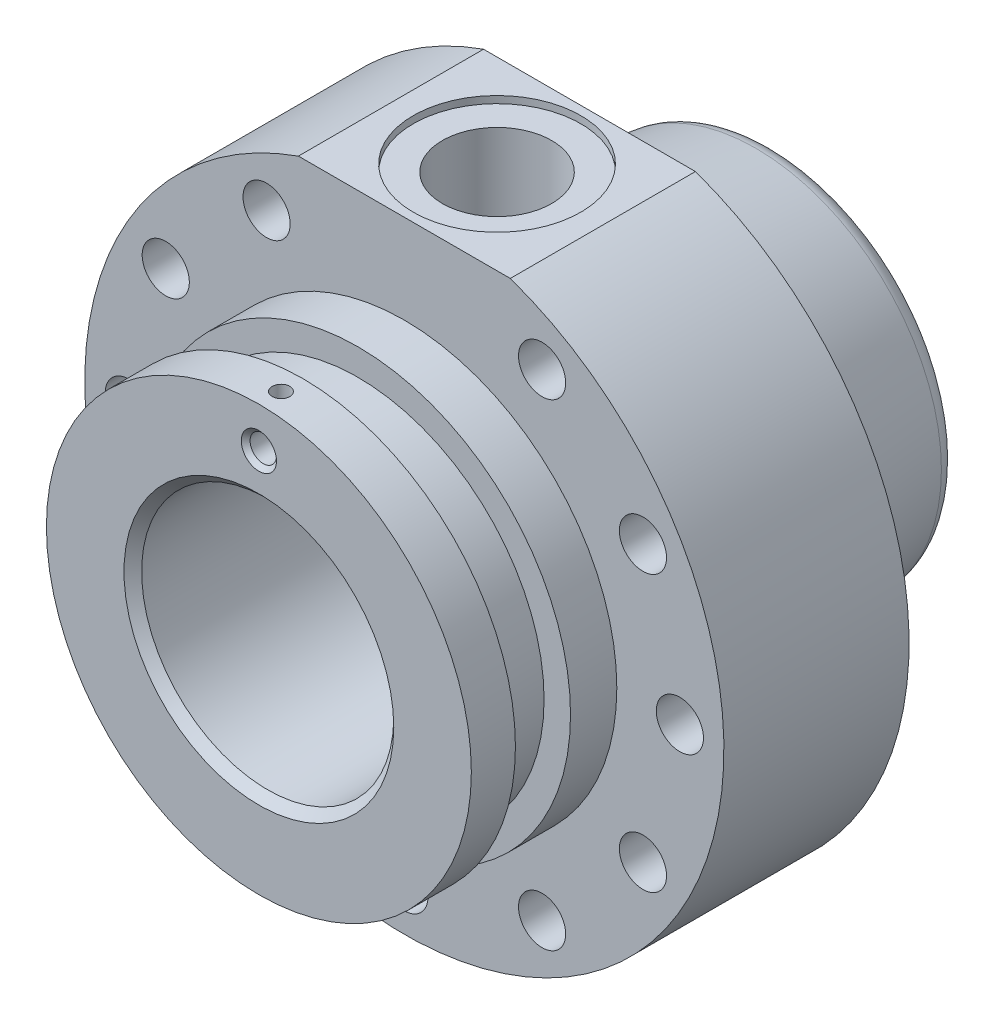
SolidWorks part; units mm, degrees
ref_plane "Płaszczyzna przednia" through (0, 0, 0) normal (0, 0, 1) x (1, 0, 0)
ref_plane "Płaszczyzna górna" through (0, 0, 0) normal (0, 1, 0) x (1, 0, 0)
ref_plane "Płaszczyzna prawa" through (0, 0, 0) normal (1, 0, 0) x (0, 0, -1)
sketch "Szkic1" plane through (0, 0, 0) normal (0, 0, 1) x (1, 0, 0)
  circle A0 centre (0, 0) radius 72.5
  dimension "D1" = 145
extrude "Dodanie-wyciągnięcie1" add sketch "Szkic1" along normal blind 42
sketch "Szkic2" plane through (0, 0, 42) normal (0, 0, 1) x (1, 0, 0)
  circle A0 centre (0, 0) radius 48.2
  dimension "D1" = 96.4
extrude "Dodanie-wyciągnięcie2" add sketch "Szkic2" along normal blind 33
sketch "Szkic3" plane through (0, 0, 0) normal (1, 0, 0) x (0, 0, -1)
  line L0 (0, 47.6) -> (42, 41.5)
  line L1 (0, -72.5) -> (0, 72.5) construction
  line L2 (42, 41.5) -> (42, 28.6)
  line L3 (42, 28.6) -> (0, 28.6)
  line L4 (0, 28.6) -> (0, 47.6)
  line L5 (0, 0) -> (74.7279, 0) construction
  dimension "D1" = 47.6
  dimension "D2" = 28.6
  dimension "D3" = 42
  dimension "D4" = 41.5
revolve "Obrót1" add sketch "Szkic3" angle 360 about L5
sketch "Szkic4" plane through (0, 0, 75) normal (0, 0, 1) x (1, 0, 0)
  circle A0 centre (0, 0) radius 28.6
  dimension "D1" = 57.2
extrude "Wytnij-wyciągnięcie1" cut sketch "Szkic4" against normal through all
sketch "Szkic5" plane through (0, 0, -42) normal (0, 0, -1) x (-1, 0, 0)
  circle A0 centre (0, 0) radius 35
  dimension "D1" = 70
extrude "Wytnij-wyciągnięcie2" cut sketch "Szkic5" against normal blind 8
sketch "Szkic6" plane through (0, 0, 0) normal (1, 0, 0) x (0, 0, -1)
  line L0 (-78.9836, 0) -> (0, 0) construction
  line L1 (-42, 48.2) -> (-75, 48.2) construction
  line L2 (-65, 48.2) -> (-52.5, 48.2)
  line L3 (-65, 48.2) -> (-65, 42.2)
  line L4 (-65, 42.2) -> (-52.5, 42.2)
  line L5 (-52.5, 48.2) -> (-52.5, 42.2)
  line L6 (-75, 48.2) -> (-75, -48.2) construction
  dimension "D1" = 6
  dimension "D2" = 10
  dimension "D3" = 12.5
revolve "Wycięcie-obrót1" cut sketch "Szkic6" angle 360 about L0
fillet "Zaokrąglenie1" radius 5 1 edges at (41.5, 0, -42)
sketch "Szkic7" plane through (0, 0, 42) normal (0, 0, 1) x (1, 0, 0)
  circle A0 centre (0, 0) radius 62.5 construction
  circle A1 centre (0, 62.5) radius 5.35
  dimension "D1" = 125
  dimension "D2" = 10.7
extrude "Wytnij-wyciągnięcie3" cut sketch "Szkic7" against normal through all
pattern_circular "Szyk kołowy1" count 12 over 360 about axis through (0, 0, 0) along (0, 0, 1) of "Wytnij-wyciągnięcie3"
chamfer "Sfazowanie1" distance 2 angle 45 1 edges at (28.6, 0, 75)
ref_plane "Płaszczyzna1" through (0, 70, 0) normal (0, 1, 0) x (1, 0, 0)
sketch "Szkic8" plane through (0, 70, 0) normal (0, 1, 0) x (1, 0, 0)
  line L1 (-25.5, -50.6911) -> (25.5, -50.6911)
  line L2 (-25.5, -50.6911) -> (-25.5, 8.8965)
  line L3 (-25.5, 8.8965) -> (25.5, 8.8965)
  line L4 (25.5, -50.6911) -> (25.5, 8.8965)
  line L5 (-25.5, -50.6911) -> (25.5, 8.8965) construction
  line L6 (-25.5, 8.8965) -> (25.5, -50.6911) construction
  point P0 (0, -20.8973)
  point P5 (0, 0)
  dimension "D1" = 51
extrude "Wytnij-wyciągnięcie4" cut sketch "Szkic8" against normal blind 1.6 and the other way blind 40
sketch "Szkic9" plane through (0, 68.4, 0) normal (0, 1, 0) x (1, 0, 0)
  circle A0 centre (0.0277, -21) radius 19
  dimension "D1" = 38
extrude "Wytnij-wyciągnięcie5" cut sketch "Szkic9" against normal blind 1.6
sketch "Szkic14" plane through (0, 0, 42) normal (0, 0, 1) x (1, 0, 0)
  line L1 (24.0352, 68.4) -> (-24.0352, 68.4)
  line L2 (24.0352, 68.4) -> (-24.0352, 68.4)
  circle A0 centre (0, 62.5) radius 5.35 construction
  arc A1 (-24.0352, 68.4) -> (24.0352, 68.4) centre (0, 0) ccw
  arc A2 (-24.0352, 68.4) -> (24.0352, 68.4) centre (0, 0) ccw
  circle A3 centre (0, 62.5) radius 5.35
  dimension "D1" = 0
extrude "Dodanie-wyciągnięcie4" add sketch "Szkic14" against normal blind 42 contours A3
sketch "Szkic15" plane through (0, 66.8, 0) normal (0, 1, 0) x (1, 0, 0)
  circle A0 centre (0.0277, -21) radius 12.4
  dimension "D1" = 24.8
extrude "Wytnij-wyciągnięcie6" cut sketch "Szkic15" against normal blind 23
sketch "Szkic16" plane through (0, 66.8, 0) normal (0, 1, 0) x (1, 0, 0)
  circle A0 centre (0.0277, -21) radius 19
extrude "Wytnij-wyciągnięcie7" cut sketch "Szkic16" along normal blind 23
sketch "Szkic17" plane through (0, 43.8, 0) normal (0, 1, 0) x (1, 0, 0)
  circle A0 centre (0.0277, -21) radius 7.5
  dimension "D1" = 15
extrude "Wytnij-wyciągnięcie8" cut sketch "Szkic17" against normal blind 23
sketch "Szkic18" plane through (0, 0, 75) normal (0, 0, 1) x (1, 0, 0)
  circle A0 centre (0, 39) radius 3
  point P2 (0, 0)
  dimension "D1" = 6
  dimension "D2" = 39
extrude "Wytnij-wyciągnięcie9" cut sketch "Szkic18" against normal up to surface (47.1141 mm away)
chamfer "Sfazowanie2" distance 1 angle 45 1 edges at (3, 39, 75)
sketch "Szkic19" plane through (0, 0, 0) normal (0, 1, 0) x (1, 0, 0)
  line L1 (-30.6, -75) -> (30.6, -75) construction
  circle A0 centre (0, -70) radius 2
  point P2 (0, 0)
  point P4 (0, 0)
  dimension "D1" = 4
  dimension "D2" = 5
extrude "Wytnij-wyciągnięcie10" cut sketch "Szkic19" along normal through all from offset 40
